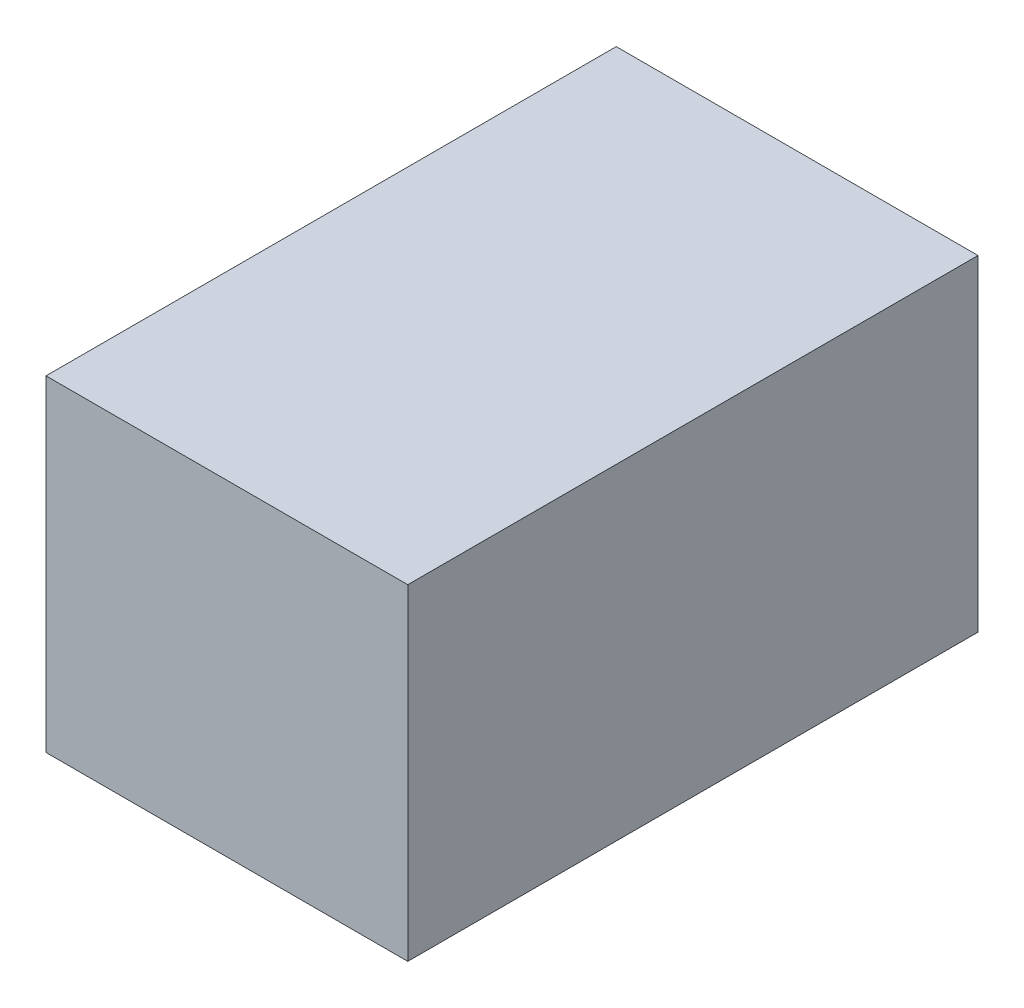
SolidWorks part; units mm, degrees
material "Rubber"
ref_plane "Front Plane" through (0, 0, 0) normal (0, 0, 1) x (1, 0, 0)
ref_plane "Top Plane" through (0, 0, 0) normal (0, 1, 0) x (1, 0, 0)
ref_plane "Right Plane" through (0, 0, 0) normal (1, 0, 0) x (0, 0, -1)
sketch "Sketch1" plane through (0, 0, 0) normal (0, 1, 0) x (1, 0, 0)
  line L1 (0, 0) -> (11.09, 0)
  line L2 (0, 0) -> (0, -17.48)
  line L3 (0, -17.48) -> (11.09, -17.48)
  line L4 (11.09, 0) -> (11.09, -17.48)
  dimension "D1" = 11.09
  dimension "D2" = 17.48
extrude "Boss-Extrude1" add sketch "Sketch1" along normal blind 10
